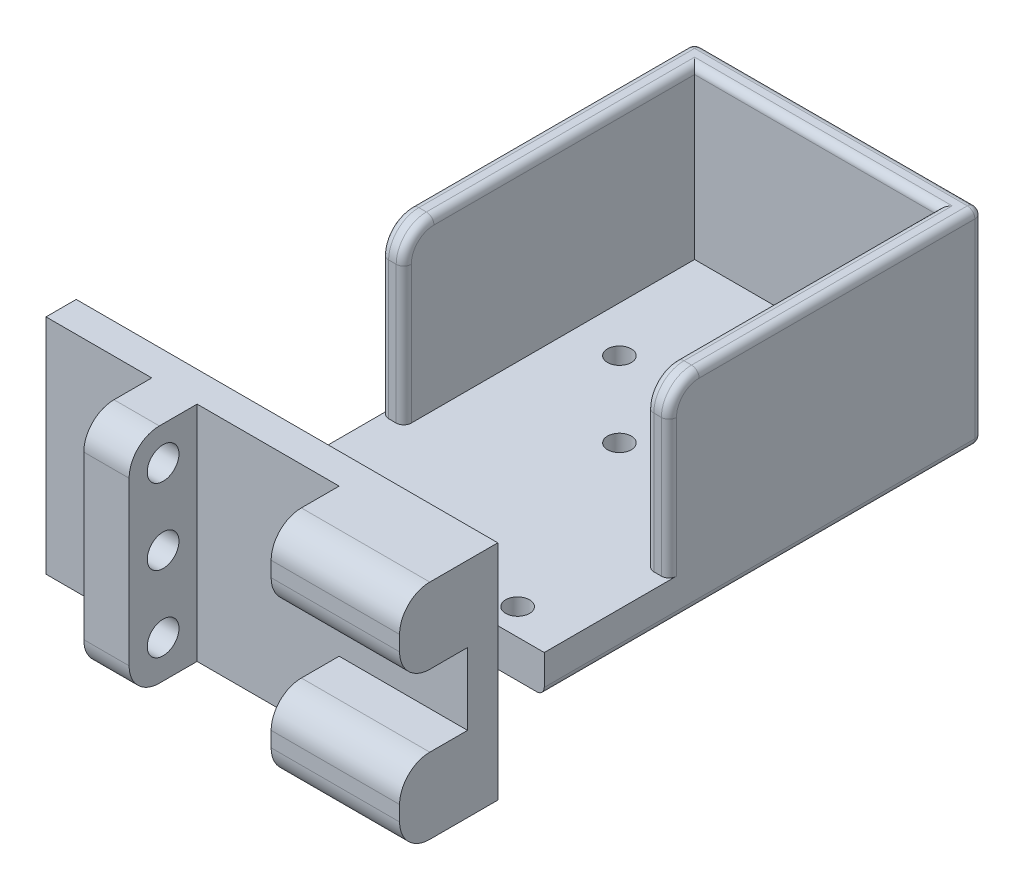
SolidWorks part; units mm, degrees
ref_plane "前视基准面" through (0, 0, 0) normal (0, 0, 1) x (1, 0, 0)
ref_plane "上视基准面" through (0, 0, 0) normal (0, 1, 0) x (1, 0, 0)
ref_plane "右视基准面" through (0, 0, 0) normal (1, 0, 0) x (0, 0, -1)
sketch "草图1" plane through (0, 0, 0) normal (0, 1, 0) x (1, 0, 0)
  line L1 (19.05, 22) -> (-19.05, 22)
  line L2 (19.05, 22) -> (19.05, -22)
  line L3 (19.05, -22) -> (-19.05, -22)
  line L4 (-19.05, 22) -> (-19.05, -22)
  line L5 (19.05, 22) -> (-19.05, -22) construction
  line L6 (19.05, -22) -> (-19.05, 22) construction
  point P0 (0, 0)
  dimension "D1" = 44
  dimension "D2" = 38.1
extrude "Sensor_base" add sketch "草图1" along normal blind 5
ref_plane "基准面1" through (0, 5, 0) normal (0, 1, 0) x (1, 0, 0)
sketch "草图2" plane through (0, 5, 0) normal (0, 1, 0) x (1, 0, 0)
  line L0 (-19.05, 22) -> (-19.05, -19.5)
  line L1 (-19.05, 22) -> (-19.05, -22) construction
  line L2 (-19.05, -19.5) -> (-16.05, -19.5)
  line L3 (-16.05, -19.5) -> (-16.05, 19)
  line L5 (19.05, -22) -> (19.05, 22) construction
  line L6 (16.05, 19) -> (16.05, -19.5)
  line L7 (16.05, -19.5) -> (19.05, -19.5)
  line L8 (19.05, -19.5) -> (19.05, 18)
  line L9 (-19.05, 22) -> (19.05, 22)
  line L10 (-16.05, 19) -> (16.05, 19)
  line L11 (19.05, 22) -> (19.05, 18)
  dimension "D1" = 3
  dimension "D2" = 38.5
  dimension "D3" = 38.5
  dimension "D4" = 3
  dimension "D5" = 3
extrude "Protector" add sketch "草图2" along normal blind 22.2
sketch "草图4" plane through (0, 5, 0) normal (0, 1, 0) x (1, 0, 0)
  line L0 (0, 19) -> (0, 13)
  line L1 (-16.05, 19) -> (16.05, 19) construction
  line L2 (0, 13) -> (0, -7)
  line L3 (0, 3) -> (10, 3)
  line L4 (0, 3) -> (-10, 3)
  line L5 (-16.05, 19) -> (16.05, 19) construction
  circle A0 centre (0, 13) radius 1.575
  circle A1 centre (-10, 3) radius 1.575
  circle A2 centre (10, 3) radius 1.575
  circle A3 centre (0, -7) radius 1.575
  dimension "D1" = 3.15
  dimension "D2" = 6
  dimension "D3" = 20
  dimension "D4" = 10
  dimension "D5" = 10
extrude "切除-拉伸1" cut sketch "草图4" against normal through all
ref_plane "基准面2" through (0, 0, 22) normal (0, 0, 1) x (1, 0, 0)
sketch "草图5" plane through (0, 0, 22) normal (0, 0, 1) x (1, 0, 0)
  line L1 (-19.05, 5) -> (19.05, 5)
  line L2 (-19.05, 5) -> (-19.05, 0)
  line L3 (-19.05, 0) -> (19.05, 0)
  line L4 (19.05, 5) -> (19.05, 0)
extrude "凸台-拉伸3" add sketch "草图5" along normal blind 29
ref_plane "基准面3" through (0, 0, 51) normal (0, 0, 1) x (1, 0, 0)
sketch "草图8" plane through (0, 0, 51) normal (0, 0, 1) x (1, 0, 0)
  line L0 (0, 0) -> (-27.9, 0)
  line L1 (0, 0) -> (27.9, 0)
  line L2 (27.9, 0) -> (27.9, 29.5)
  line L3 (27.9, 29.5) -> (-27.9, 29.5)
  line L4 (-27.9, 29.5) -> (-27.9, 0)
extrude "凸台-拉伸4" add sketch "草图8" along normal blind 4
ref_plane "基准面4" through (0, 0, 55) normal (0, 0, 1) x (1, 0, 0)
sketch "草图9" plane through (0, 0, 55) normal (0, 0, 1) x (1, 0, 0)
  line L0 (-27.9, 0) -> (-13.9, 0)
  line L1 (-27.9, 0) -> (27.9, 0) construction
  line L2 (-13.9, 0) -> (-13.9, 29.5)
  line L3 (27.9, 29.5) -> (-27.9, 29.5) construction
  line L4 (-13.9, 29.5) -> (-7.9, 29.5)
  line L5 (-7.9, 29.5) -> (-7.9, 0)
  line L6 (-7.9, 0) -> (-13.9, 0)
  dimension "D1" = 14
extrude "凸台-拉伸5" add sketch "草图9" along normal blind 9 contours L6 L5 L4 L2
sketch "草图10" plane through (0, 0, 55) normal (0, 0, 1) x (1, 0, 0)
  line L0 (27.9, 29.5) -> (27.9, 19.5)
  line L1 (27.9, 0) -> (27.9, 29.5) construction
  line L2 (27.9, 0) -> (27.9, 10)
  line L3 (27.9, 10) -> (10.9, 10)
  line L4 (10.9, 10) -> (10.9, 0)
  line L5 (-7.9, 0) -> (27.9, 0) construction
  line L6 (10.9, 0) -> (27.9, 0)
  line L7 (27.9, 19.5) -> (10.9, 19.5)
  line L8 (10.9, 19.5) -> (10.9, 29.5)
  line L9 (27.9, 29.5) -> (-7.9, 29.5) construction
  line L10 (10.9, 29.5) -> (27.9, 29.5)
extrude "凸台-拉伸6" add sketch "草图10" along normal blind 9
fillet "圆角2" radius 4 1 edges at (19.4, 29.5, 64)
fillet "圆角3" radius 4 1 edges at (19.4, 19.5, 64)
fillet "圆角4" radius 4 2 edges at (19.4, 0, 64) (19.4, 10, 64)
fillet "圆角5" radius 4 2 edges at (-10.9, 0, 64) (-10.9, 29.5, 64)
ref_plane "基准面5" through (-13.9, 0, 0) normal (-1, 0, 0) x (0, 0, 1)
ref_plane "基准面6" through (0, 5, 0) normal (0, 1, 0) x (1, 0, 0)
ref_plane "基准面7" through (0, 5, 0) normal (0, 1, 0) x (1, 0, 0)
ref_plane "基准面8" through (0, 5, 0) normal (0, 1, 0) x (1, 0, 0)
ref_plane "基准面9" through (27.9, 0, 0) normal (1, 0, 0) x (0, 0, -1)
ref_plane "基准面10" through (19.05, 0, 0) normal (1, 0, 0) x (0, 0, -1)
fillet "圆角6" radius 4 2 edges at (-17.55, 27.2, 19.5) (17.55, 27.2, 19.5)
ref_plane "基准面11" through (0, 0, 0) normal (0, -1, 0) x (-1, 0, 0)
sketch "草图25" plane through (0, 0, 0) normal (0, -1, 0) x (-1, 0, 0)
  line L0 (19.05, 22) -> (19.05, -44)
  line L1 (19.05, 22) -> (19.05, -51) construction
  line L2 (19.05, -44) -> (19.05, -51)
  line L3 (19.05, -51) -> (27.9, -51)
  line L4 (27.9, -51) -> (19.05, -44)
  dimension "D1" = 7
extrude "凸台-拉伸12" [suppressed] add sketch "草图25" against normal blind 5 contours L3 L4 L2
ref_plane "基准面12" through (-13.9, 0, 0) normal (-1, 0, 0) x (0, 0, 1)
sketch "草图26" plane through (-13.9, 0, 0) normal (-1, 0, 0) x (0, 0, 1)
  line L0 (64, 4) -> (64, 0)
  line L1 (59.5, 5) -> (59.5, 15)
  line L2 (64, 0) -> (59.5, 0)
  line L3 (64, 0) -> (64, 5)
  line L4 (64, 5) -> (59.5, 5)
  line L5 (59.5, 0) -> (59.5, 5)
  line L6 (59.5, 15) -> (59.5, 25)
  line L7 (60, 29.5) -> (55, 29.5) construction
  circle A0 centre (59.5, 5) radius 2.1
  circle A1 centre (59.5, 15) radius 2.1
  circle A2 centre (59.5, 25) radius 2.1
  dimension "D1" = 4.2
  dimension "D2" = 4.2
  dimension "D3" = 4.2
  dimension "D4" = 4.5
extrude "切除-拉伸6" cut sketch "草图26" against normal up to next
sketch "草图30" plane through (0, 5, 0) normal (0, 1, 0) x (1, 0, 0)
  line L0 (19.05, -51) -> (19.05, -44)
  line L1 (19.05, -51) -> (19.05, -19.5) construction
  line L2 (19.05, -44) -> (0, -44)
  line L3 (0, -44) -> (-5, -44)
  line L4 (-5, -44) -> (-5, -36)
  line L5 (-5, -36) -> (5, -36)
  line L6 (5, -36) -> (5, -44)
  line L7 (5, -36) -> (19.05, -36)
  line L8 (19.05, -36) -> (19.05, -44)
  line L9 (19.05, -51) -> (-19.05, -51) construction
  dimension "D1" = 7
  dimension "D2" = 8
  dimension "D3" = 14.05
extrude "切除-拉伸7" cut sketch "草图30" against normal blind 5 contours L6 L5 L4 L3 L2 | L8 L7 L6 L2
sketch "草图31" plane through (0, 5, 0) normal (0, 1, 0) x (1, 0, 0)
  line L0 (19.05, -51) -> (5, -51)
  line L1 (19.05, -51) -> (-19.05, -51) construction
  line L2 (5, -51) -> (5, -44)
  line L3 (19.05, -44) -> (-5, -44) construction
  line L4 (5, -44) -> (19.05, -44)
  line L5 (19.05, -44) -> (19.05, -51)
  line L6 (5, -44) -> (19.05, -51)
  line L7 (19.05, -36) -> (5, -36)
  line L8 (-5, -36) -> (19.05, -36) construction
  line L9 (5, -36) -> (5, -29)
  line L10 (5, -29) -> (19.05, -29)
  line L11 (19.05, -36) -> (19.05, -19.5) construction
  line L12 (19.05, -29) -> (19.05, -36)
  line L13 (5, -29) -> (19.05, -36)
  circle A0 centre (12.025, -32.5) radius 1.575
  circle A1 centre (12.025, -47.5) radius 1.575
extrude "切除-拉伸8" cut sketch "草图31" against normal up to next contours A0 | A1
ref_plane "基准面13" through (19.05, 0, 0) normal (1, 0, 0) x (0, 0, -1)
sketch "草图34" plane through (19.05, 0, 0) normal (1, 0, 0) x (0, 0, -1)
  line L0 (-19.5, 14.1) -> (-51, 29.5)
  line L1 (-19.5, 23.2) -> (-19.5, 5) construction
  line L2 (-51, 29.5) -> (-51, 5)
  line L3 (-51, 5) -> (-19.5, 5)
  line L4 (-19.5, 5) -> (-19.5, 14.1)
extrude "凸台-拉伸13" [suppressed] add sketch "草图34" against normal blind 3
mirror "镜向3" [suppressed] about plane through (0, 0, 0) normal (1, 0, 0)
ref_plane "基准面14" through (0, 0, 0) normal (0, -1, 0) x (-1, 0, 0)
sketch "草图35" plane through (0, 0, 0) normal (0, -1, 0) x (-1, 0, 0)
  line L0 (-19.05, -44) -> (-27.9, -51)
  line L1 (-27.9, -51) -> (-19.05, -51)
  line L2 (-19.05, -51) -> (-19.05, -44)
extrude "凸台-拉伸14" [suppressed] add sketch "草图35" against normal blind 5
fillet "圆角7" radius 1 1 edges at (19.05, 13.6, -22)
fillet "圆角8" radius 1 5 edges at (19.05, 0, 7.5) (18.7571, 0, -21.7071) (-19.05, 0, 14.5) (-0.5, 0, -22) (-19.05, 13.6, -22)
fillet "圆角9" radius 1 16 edges at (-16.05, 14.1, 19.5) (-16.05, 26.0284, 18.3284) (16.05, 14.1, 19.5) (16.05, 26.0284, 18.3284) (19.05, 14.1, 19.5) (19.05, 26.0284, 18.3284) (19.05, 27.2, -2.75) (18.7571, 27.2, -21.7071) (0, 27.2, -22) (-18.7571, 27.2, -21.7071) (-19.05, 14.1, 19.5) (-19.05, 26.0284, 18.3284) (0, 27.2, -19) (-16.05, 27.2, -1.75) (16.05, 27.2, -1.75) (-19.05, 27.2, -2.75)
fillet "圆角10" [suppressed] radius 1
fillet "圆角11" [suppressed] radius 1
fillet "圆角12" [suppressed] radius 1
sketch "Sketch1" plane through (0, 0, 0) normal (0, -1, 0) x (1, 0, 0)
  line L0 (-13.9, 55) -> (-27.9, 55)
sketch "Sketch2" plane through (0, 0, 0) normal (0, -1, 0) x (-1, 0, 0)
  line L0 (13.9, -55) -> (27.9, -55)
sketch "Sketch3" plane through (0, 0, 51) normal (0, 0, -1) x (-1, 0, 0)
  line L0 (27.9, 0) -> (27.9, 29.5)
  line L1 (27.9, 29.5) -> (-27.9, 29.5)
sketch "Sketch4" plane through (0, 0, 55) normal (0, 0, 1) x (1, 0, 0)
  line L0 (-27.9, 0) -> (-13.9, 0)
  line L1 (-7.9, 0) -> (10.9, 0)
  line L2 (-7.9, 0) -> (-13.9, 0)
sketch "Sketch7" plane through (-13.9, 0, 0) normal (-1, 0, 0) x (0, 0, 1)
  line L0 (64, 4) -> (55, 4)
  line L1 (55, 0) -> (55, 29.5) construction
